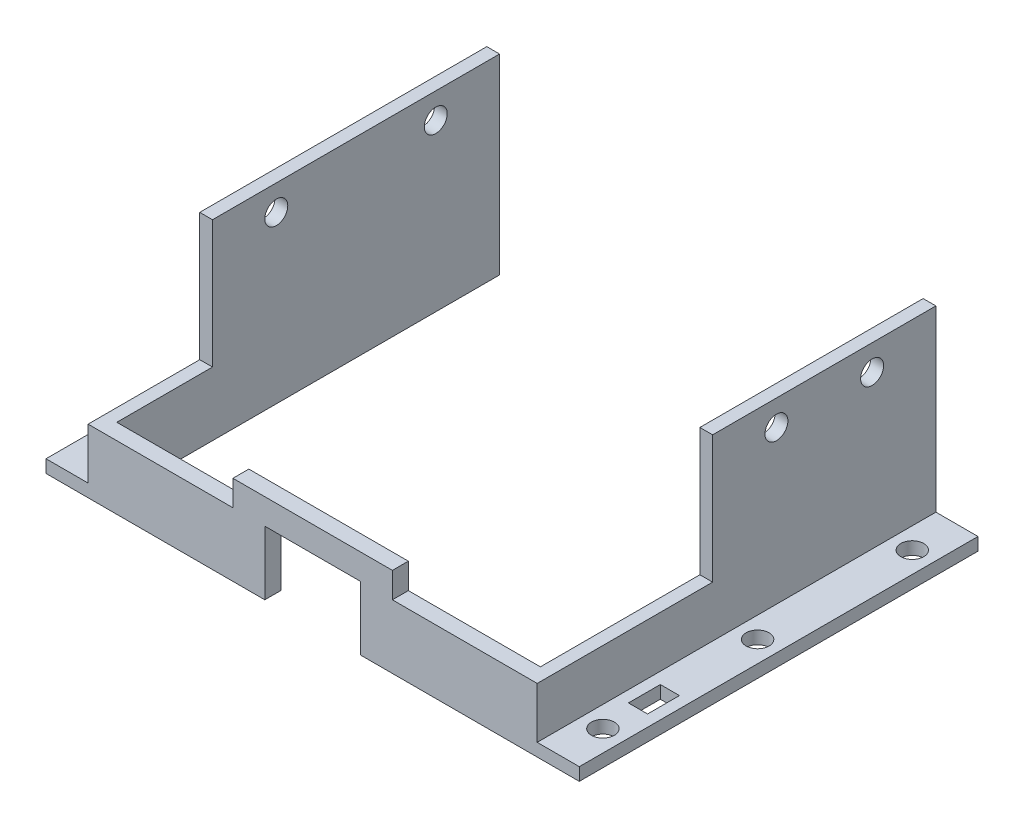
SolidWorks part; units mm, degrees
ref_plane "前视基准面" through (0, 0, 0) normal (0, 0, 1) x (1, 0, 0)
ref_plane "上视基准面" through (0, 0, 0) normal (0, 1, 0) x (1, 0, 0)
ref_plane "右视基准面" through (0, 0, 0) normal (1, 0, 0) x (0, 0, -1)
sketch "Sketch1" plane through (0, 0, 0) normal (0, 1, 0) x (1, 0, 0)
  line L1 (0, 0) -> (70.4, 0)
  line L2 (0, 0) -> (0, 2)
  line L3 (0, 2) -> (70.4, 2)
  line L4 (70.4, 0) -> (70.4, 2)
  dimension "D1" = 70.4
  dimension "D2" = 2
extrude "Boss-Extrude2" add sketch "Sketch1" along normal blind 10
sketch "Sketch2" plane through (0, 10, 0) normal (0, 1, 0) x (1, 0, 0)
  line L1 (0, 2) -> (2, 2)
  line L2 (0, 2) -> (0, 57)
  line L3 (0, 57) -> (2, 57)
  line L4 (2, 2) -> (2, 57)
  line L5 (70.4, 2) -> (68.4, 2)
  line L6 (70.4, 2) -> (70.4, 57)
  line L7 (70.4, 57) -> (68.4, 57)
  line L8 (68.4, 2) -> (68.4, 57)
  dimension "D1" = 55
  dimension "D2" = 2
  dimension "D3" = 2
extrude "Boss-Extrude3" add sketch "Sketch2" against normal blind 10
sketch "Sketch3" plane through (0, 0, 0) normal (0, 0, 1) x (1, 0, 0)
  line L0 (35.2, 0) -> (35.2, 21.6902) construction
  line L1 (0, 0) -> (70.4, 0) construction
  line L2 (0, 10) -> (70.4, 10) construction
  line L3 (25.7, 10) -> (44.7, 10)
  line L4 (25.7, 10) -> (25.7, 13)
  line L5 (25.7, 13) -> (44.7, 13)
  line L6 (44.7, 10) -> (44.7, 13)
  dimension "D1" = 9.5
  dimension "D2" = 9.5
  dimension "D3" = 3
extrude "Boss-Extrude4" add sketch "Sketch3" against normal blind 2
sketch "Sketch4" plane through (0, 0, 0) normal (0, 0, 1) x (1, 0, 0)
  line L0 (35.2, 0) -> (35.2, 21.4055) construction
  line L1 (0, 0) -> (70.4, 0) construction
  line L3 (27.7, 0) -> (42.7, 0)
  line L4 (27.7, 0) -> (27.7, 10)
  line L5 (27.7, 10) -> (42.7, 10)
  line L6 (42.7, 0) -> (42.7, 10)
  dimension "D1" = 10
  dimension "D2" = 7.5
  dimension "D3" = 7.5
extrude "Cut-Extrude2" cut sketch "Sketch4" against normal blind 2
sketch "Sketch5" plane through (25.7, 0, 0) normal (-1, 0, 0) x (0, 0, 1)
  line L1 (-2, 13) -> (0, 13)
  line L2 (-2, 13) -> (-2, 10)
  line L3 (-2, 10) -> (0, 10)
  line L4 (0, 13) -> (0, 10)
extrude "Boss-Extrude5" add sketch "Sketch5" along normal blind 1
sketch "Sketch6" plane through (44.7, 0, 0) normal (1, 0, 0) x (0, 0, -1)
  line L1 (0, 13) -> (2, 13)
  line L2 (0, 13) -> (0, 10)
  line L3 (0, 10) -> (2, 10)
  line L4 (2, 13) -> (2, 10)
extrude "Boss-Extrude6" add sketch "Sketch6" along normal blind 1
sketch "Sketch7" plane through (0, 0, 0) normal (-1, 0, 0) x (0, 0, 1)
  line L0 (0, 10) -> (0, 0) construction
  line L1 (-57, 0) -> (0, 0)
  line L2 (-57, 0) -> (-57, 2)
  line L3 (-57, 2) -> (0, 2)
  line L4 (0, 0) -> (0, 2)
  dimension "D1" = 2
extrude "Boss-Extrude7" add sketch "Sketch7" along normal blind 6.6
sketch "Sketch8" plane through (70.4, 0, 0) normal (1, 0, 0) x (0, 0, -1)
  line L0 (57, 0) -> (57, 10) construction
  line L1 (0, 0) -> (57, 0)
  line L2 (0, 0) -> (0, 2)
  line L3 (0, 2) -> (57, 2)
  line L4 (57, 0) -> (57, 2)
  dimension "D1" = 2
extrude "Boss-Extrude8" add sketch "Sketch8" along normal blind 6.6
sketch "Sketch10" plane through (0, 0, -57) normal (0, 0, -1) x (-1, 0, 0)
  line L0 (-2, 10) -> (-2, 0)
  line L1 (-2, 0) -> (6.6, 0)
  line L2 (6.6, 0) -> (6.6, 2)
  line L3 (6.6, 2) -> (0, 2)
  line L4 (0, 2) -> (0, 10)
  line L5 (0, 10) -> (-2, 10)
  line L6 (-77, 0) -> (-68.4, 0)
  line L7 (-68.4, 0) -> (-68.4, 10)
  line L8 (-68.4, 10) -> (-70.4, 10)
  line L9 (-70.4, 10) -> (-70.4, 2)
  line L10 (-70.4, 2) -> (-77, 2)
  line L11 (-77, 2) -> (-77, 0)
extrude "Boss-Extrude9" add sketch "Sketch10" along normal blind 5
sketch "Sketch12" plane through (0, 10, 0) normal (0, 1, 0) x (1, 0, 0)
  line L0 (0, 0) -> (0, 62) construction
  line L1 (0, 57) -> (2, 57)
  line L2 (0, 57) -> (0, 17)
  line L3 (0, 17) -> (2, 17)
  line L4 (2, 57) -> (2, 17)
  line L5 (2, 2) -> (2, 62) construction
  line L6 (0, 62) -> (2, 62) construction
  line L7 (68.4, 62) -> (68.4, 2) construction
  line L8 (68.4, 57) -> (70.4, 57)
  line L9 (68.4, 57) -> (68.4, 27)
  line L10 (68.4, 27) -> (70.4, 27)
  line L11 (70.4, 57) -> (70.4, 27)
  line L12 (70.4, 62) -> (70.4, 0) construction
  line L13 (68.4, 62) -> (70.4, 62) construction
  line L15 (2, 62) -> (0, 62)
  line L16 (2, 62) -> (2, 57)
  line L17 (2, 57) -> (0, 57)
  line L18 (0, 62) -> (0, 57)
  line L19 (70.4, 62) -> (68.4, 62)
  line L20 (70.4, 62) -> (70.4, 57)
  line L21 (70.4, 57) -> (68.4, 57)
  line L22 (68.4, 62) -> (68.4, 57)
  line M4 (2, 2) -> (2, 62)
  line M5 (2, 62) -> (0, 62)
  line M6 (0, 62) -> (0, 0)
  dimension "D1" = 5
  dimension "D2" = 40
  dimension "D3" = 5
  dimension "D4" = 30
extrude "Boss-Extrude10" add sketch "Sketch12" along normal blind 20 contours L1 M6 M4 M5 | L3 L1 M6 M4 | L11 L8 L9 L10 | L19 L22 L8 L20
sketch "Sketch13" plane through (0, 30, 0) normal (0, 1, 0) x (1, 0, 0)
  line L0 (35.2, 2) -> (35.2, 63.9637) construction
  line L1 (45.7, 2) -> (24.7, 2) construction
  line L2 (0, 17) -> (35.2, 17)
  line L3 (35.2, 17) -> (35.2, 27)
  line L4 (35.2, 27) -> (70.4, 27)
  line L5 (70.4, 27) -> (70.4, 62)
  line L6 (70.4, 62) -> (0, 62)
  line L7 (0, 62) -> (0, 17)
extrude "Boss-Extrude11" add sketch "Sketch13" along normal blind 3
sketch "Sketch14" plane through (0, 33, 0) normal (0, 1, 0) x (1, 0, 0)
  line L0 (35.2, 62) -> (35.2, 11.7147) construction
  line L1 (70.4, 62) -> (0, 62) construction
  line L2 (10.2, 62) -> (10.2, 11.7147) construction
  line L3 (60.2, 62) -> (60.2, 11.7147) construction
  line L4 (10.2, 57) -> (60.2, 57) construction
  line L5 (11.7, 57) -> (11.7, 17) construction
  line L6 (0, 17) -> (35.2, 17) construction
  line L7 (58.2, 57) -> (58.2, 27) construction
  line L8 (35.2, 27) -> (70.4, 27) construction
  line L10 (11.45, 55.5) -> (11.95, 55.5)
  line L11 (11.45, 55.5) -> (11.45, 46.5)
  line L12 (11.45, 46.5) -> (11.95, 46.5)
  line L13 (11.95, 55.5) -> (11.95, 46.5)
  line L14 (11.45, 42.5) -> (11.95, 42.5)
  line L15 (11.45, 42.5) -> (11.45, 33.5)
  line L16 (11.45, 33.5) -> (11.95, 33.5)
  line L17 (11.95, 42.5) -> (11.95, 33.5)
  line L18 (11.45, 30) -> (11.95, 30)
  line L19 (11.45, 30) -> (11.45, 21)
  line L20 (11.45, 21) -> (11.95, 21)
  line L21 (11.95, 30) -> (11.95, 21)
  line L22 (57.95, 55.5) -> (58.45, 55.5)
  line L23 (57.95, 55.5) -> (57.95, 46.5)
  line L24 (57.95, 46.5) -> (58.45, 46.5)
  line L25 (58.45, 55.5) -> (58.45, 46.5)
  line L26 (57.95, 42.5) -> (58.45, 42.5)
  line L27 (57.95, 42.5) -> (57.95, 33.5)
  line L28 (57.95, 33.5) -> (58.45, 33.5)
  line L29 (58.45, 42.5) -> (58.45, 33.5)
  dimension "D1" = 25
  dimension "D2" = 25
  dimension "D3" = 5
  dimension "D4" = 1.5
  dimension "D5" = 2
  dimension "D6" = 0.5
  dimension "D7" = 0.25
  dimension "D8" = 1.5
  dimension "D9" = 9
  dimension "D10" = 4
  dimension "D11" = 9
  dimension "D12" = 9
  dimension "D13" = 3.5
  dimension "D14" = 1.5
  dimension "D15" = 0.25
  dimension "D16" = 0.25
  dimension "D17" = 9
  dimension "D18" = 4
extrude "Cut-Extrude3" cut sketch "Sketch14" against normal blind 3
sketch "Sketch15" plane through (0, 33, 0) normal (0, 1, 0) x (1, 0, 0)
  line L0 (70.4, 62) -> (0, 62) construction
  line L1 (16, 62) -> (54.4, 62)
  line L2 (16, 62) -> (16, 17)
  line L3 (16, 17) -> (54.4, 17)
  line L4 (54.4, 62) -> (54.4, 17)
  line L5 (0, 62) -> (0, 17) construction
  line L6 (70.4, 62) -> (70.4, 0) construction
  dimension "D1" = 16
  dimension "D2" = 16
extrude "Cut-Extrude4" cut sketch "Sketch15" against normal blind 3
sketch "Sketch16" plane through (0, 0, 0) normal (0, 0, 1) x (1, 0, 0)
  line L0 (-6.6, 0) -> (27.7, 0)
  line L1 (27.7, 0) -> (27.7, 10)
  line L2 (27.7, 10) -> (42.7, 10)
  line L3 (42.7, 10) -> (42.7, 0)
  line L4 (42.7, 0) -> (77, 0)
  line L5 (77, 0) -> (77, 2)
  line L6 (77, 2) -> (70.4, 2)
  line L7 (70.4, 2) -> (70.4, 10)
  line L8 (70.4, 10) -> (45.7, 10)
  line L9 (45.7, 10) -> (45.7, 13)
  line L10 (45.7, 13) -> (24.7, 13)
  line L11 (24.7, 13) -> (24.7, 10)
  line L12 (24.7, 10) -> (0, 10)
  line L13 (0, 10) -> (0, 2)
  line L14 (0, 2) -> (-6.6, 2)
  line L15 (-6.6, 2) -> (-6.6, 0)
extrude "Boss-Extrude12" add sketch "Sketch16" along normal blind 0.5
sketch "Sketch17" plane through (0, 2, 0) normal (0, 1, 0) x (1, 0, 0)
  line L0 (-3.3, -0.5) -> (-3.3, 64.6995) construction
  line L1 (0, -0.5) -> (-6.6, -0.5) construction
  line L2 (73.7, -0.5) -> (73.7, 65.8086) construction
  line L3 (77, -0.5) -> (70.4, -0.5) construction
  line L4 (-6.6, 62) -> (0, 62) construction
  line L5 (70.4, 62) -> (77, 62) construction
  line L6 (0, 17) -> (16, 17) construction
  line L7 (-4.8, 17) -> (-1.8, 17)
  line L8 (-4.8, 17) -> (-4.8, 12)
  line L9 (-4.8, 12) -> (-1.8, 12)
  line L10 (-1.8, 17) -> (-1.8, 12)
  line L12 (72.2, 17) -> (75.2, 17)
  line L13 (72.2, 17) -> (72.2, 12)
  line L14 (72.2, 12) -> (75.2, 12)
  line L15 (75.2, 17) -> (75.2, 12)
  circle A0 centre (-3.3, 55) radius 1.8
  circle A1 centre (73.7, 55) radius 1.8
  circle A2 centre (-3.3, 6.5) radius 1.8
  circle A3 centre (73.7, 6.5) radius 1.8
  circle A4 centre (-3.3, 30.75) radius 1.8
  circle A5 centre (73.7, 30.75) radius 1.8
  dimension "D1" = 3.6
  dimension "D2" = 3.6
  dimension "D3" = 3.6
  dimension "D4" = 3.6
  dimension "D9" = 3.6
  dimension "D10" = 3.6
  dimension "D5" = 7
  dimension "D6" = 7
  dimension "D7" = 7
  dimension "D8" = 7
  dimension "D11" = 1.5
  dimension "D12" = 1.5
  dimension "D13" = 5
  dimension "D14" = 0
  dimension "D15" = 1.5
  dimension "D16" = 1.5
extrude "Cut-Extrude6" cut sketch "Sketch17" against normal blind 3
sketch "Sketch18" plane through (16, 0, 0) normal (1, 0, 0) x (0, 0, -1)
  line L1 (17, 30) -> (62, 30)
  line L2 (17, 30) -> (17, 33)
  line L3 (17, 33) -> (62, 33)
  line L4 (62, 30) -> (62, 33)
extrude "Cut-Extrude7" cut sketch "Sketch18" against normal blind 44 and the other way blind 116
sketch "Sketch19" plane through (2, 0, 0) normal (1, 0, 0) x (0, 0, -1)
  line L0 (62, 26) -> (4.464, 26) construction
  line L1 (62, 30) -> (62, 0) construction
  line L2 (17, 30) -> (62, 30) construction
  line L3 (17, 30) -> (17, 10) construction
  circle A0 centre (52, 26) radius 1.8
  circle A1 centre (27, 26) radius 1.8
  point P10 (17, 20)
  dimension "D2" = 3.6
  dimension "D3" = 3.6
  dimension "D1" = 4
  dimension "D4" = 10
  dimension "D5" = 10
extrude "Cut-Extrude8" cut sketch "Sketch19" against normal blind 10
sketch "Sketch20" plane through (70.4, 0, 0) normal (1, 0, 0) x (0, 0, -1)
  line L0 (62, 26) -> (11.928, 26) construction
  line L1 (62, 30) -> (62, 2) construction
  line L2 (27, 30) -> (62, 30) construction
  line L3 (27, 30) -> (27, 10) construction
  circle A0 centre (52, 26) radius 1.8
  circle A1 centre (37, 26) radius 1.8
  dimension "D2" = 3.6
  dimension "D3" = 3.6
  dimension "D1" = 4
  dimension "D4" = 10
  dimension "D5" = 10
extrude "Cut-Extrude9" cut sketch "Sketch20" against normal blind 10
sketch "Sketch25" plane through (24.7, 0, 0) normal (-1, 0, 0) x (0, 0, 1)
  line L1 (0.5, 10) -> (-2, 10)
  line L2 (0.5, 10) -> (0.5, 14)
  line L3 (0.5, 14) -> (-2, 14)
  line L4 (-2, 10) -> (-2, 14)
  dimension "D1" = 4
extrude "Boss-Extrude15" add sketch "Sketch25" along normal blind 2 and the other way blind 23
